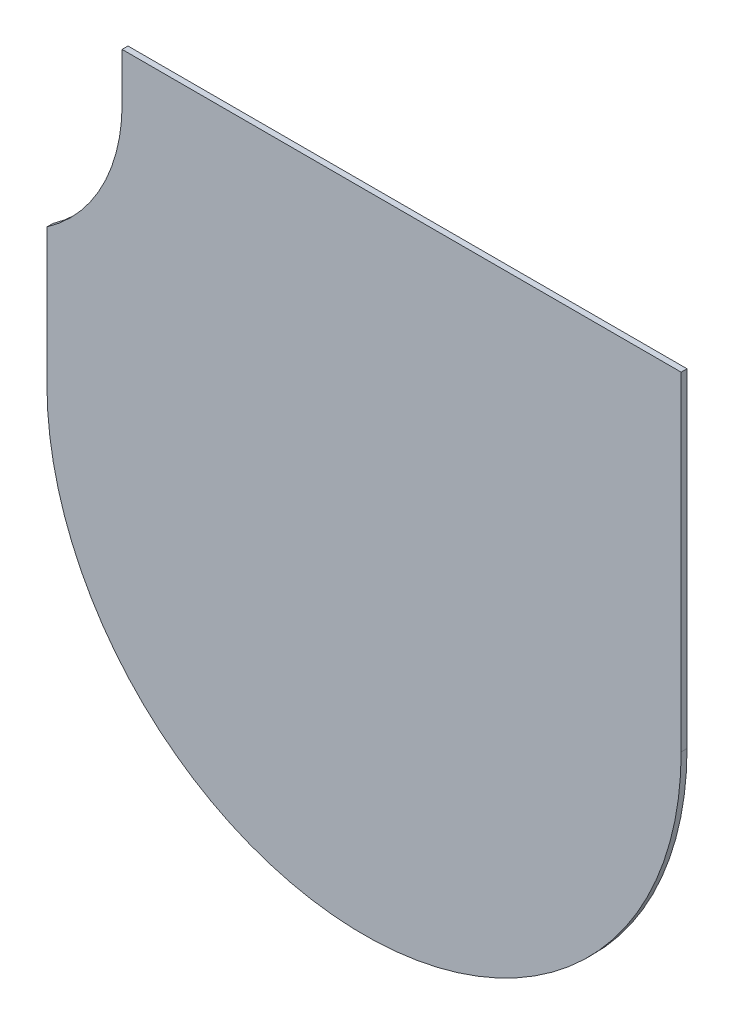
SolidWorks part; units mm, degrees
material "Acrylic (Medium-high impact)"
ref_plane "Front Plane" through (0, 0, 0) normal (0, 0, 1) x (1, 0, 0)
ref_plane "Top Plane" through (0, 0, 0) normal (0, 1, 0) x (1, 0, 0)
ref_plane "Right Plane" through (0, 0, 0) normal (1, 0, 0) x (0, 0, -1)
sketch "Sketch1" plane through (0, 0, 0) normal (0, 0, 1) x (1, 0, 0)
  line L1 (0, 0) -> (40.005, 0) construction
  line L2 (113.03, 0) -> (113.03, -76.2) construction
  line L4 (40.005, -76.2) -> (40.005, -25.8407)
  line L5 (186.055, -76.2) -> (186.055, 0)
  line L6 (186.055, 0) -> (182.88, 0) construction
  line L7 (47.625, 0) -> (186.055, 0) construction
  line L8 (47.625, 0) -> (182.88, 0) construction
  line L10 (186.055, 0) -> (47.625, 0) construction
  line L11 (186.055, 0) -> (186.055, 12.7)
  line L12 (186.055, 12.7) -> (47.625, 12.7)
  line L13 (47.625, 0) -> (47.625, 12.7)
  arc A0 (40.005, -76.2) -> (186.055, -76.2) centre (113.03, -76.2) ccw
  arc A1 (40.005, -25.8407) -> (47.625, 0) centre (0, 0) ccw
  dimension "D2" = 146.05
  dimension "D3" = 95.25
  dimension "D1" = 76.2
  dimension "D4" = 12.7
extrude "Boss-Extrude1" add sketch "Sketch1" along normal blind 1.5875
sketch "Sketch2" plane through (0, 0, 0) normal (0, 0, 1) x (1, 0, 0)
  line L0 (186.055, -76.2) -> (186.055, 12.7) construction
  line L1 (40.005, -25.8407) -> (40.005, -76.2) construction
  line L2 (186.055, 12.7) -> (47.625, 12.7) construction
  line L5 (186.055, -76.2) -> (186.055, 0)
  line L6 (186.055, 0) -> (186.055, 12.7)
  line L9 (40.005, -76.2) -> (40.005, -25.8407)
  line L10 (186.055, 12.7) -> (198.755, 12.7)
  line L11 (198.755, 12.7) -> (198.755, -76.2)
  line L12 (27.305, -39.0202) -> (27.305, -76.2)
  line L13 (27.305, -76.2) -> (40.005, -76.2) construction
  arc A2 (40.005, -76.2) -> (186.055, -76.2) centre (113.03, -76.2) ccw
  arc A4 (27.305, -39.0202) -> (40.005, -25.8407) centre (0, 0) ccw
  arc A5 (27.305, -76.2) -> (198.755, -76.2) centre (113.03, -76.2) ccw
  arc A7 (40.005, -76.2) -> (186.055, -76.2) centre (113.03, -76.2) ccw construction
  point P16 (0, 0)
  point P17 (40.005, -85.4357)
  point P20 (0, 0)
  point P22 (0, 0)
  point P26 (0, 0)
  point P27 (27.305, -30.791)
  point P28 (0, 0)
  dimension "D1" = 12.7
  dimension "D2" = 12.7
extrude "Boss-Extrude2" add sketch "Sketch2" along normal blind 1.5875
sketch "Sketch3" plane through (0, 0, 0) normal (0, 0, 1) x (1, 0, 0)
  line L0 (113.03, -59.576) -> (113.03, -177.8) construction
  line L2 (113.03, -152.4) -> (113.03, -76.2) construction
  line L3 (208.28, -139.7) -> (113.03, -139.7) construction
  line L7 (108.53, -152.4) -> (108.53, -76.2)
  line L8 (117.53, -152.4) -> (117.53, -76.2)
  line L9 (179.07, -114.3) -> (107.5796, -73.025)
  line L10 (179.07, -114.3) -> (113.03, -114.3) construction
  line L11 (179.07, -114.3) -> (201.067, -127)
  line L12 (201.067, -114.3) -> (201.067, -127) construction
  line L13 (201.067, -114.3) -> (179.07, -114.3) construction
  line L14 (201.067, -127) -> (212.5048, -133.6036)
  arc A2 (108.53, -152.4) -> (117.53, -152.4) centre (113.03, -152.4) ccw
  arc A3 (117.53, -76.2) -> (108.53, -76.2) centre (113.03, -76.2) ccw
  circle A4 centre (201.067, -114.3) radius 12.7
  point P4 (113.03, -114.3)
  dimension "D1" = 9
  dimension "D4" = 82.55
  dimension "D9" = 25.4
  dimension "D3" = 95.25
  dimension "D5" = 66.04
  dimension "D7" = 76.2
  dimension "D10" = 25.4
